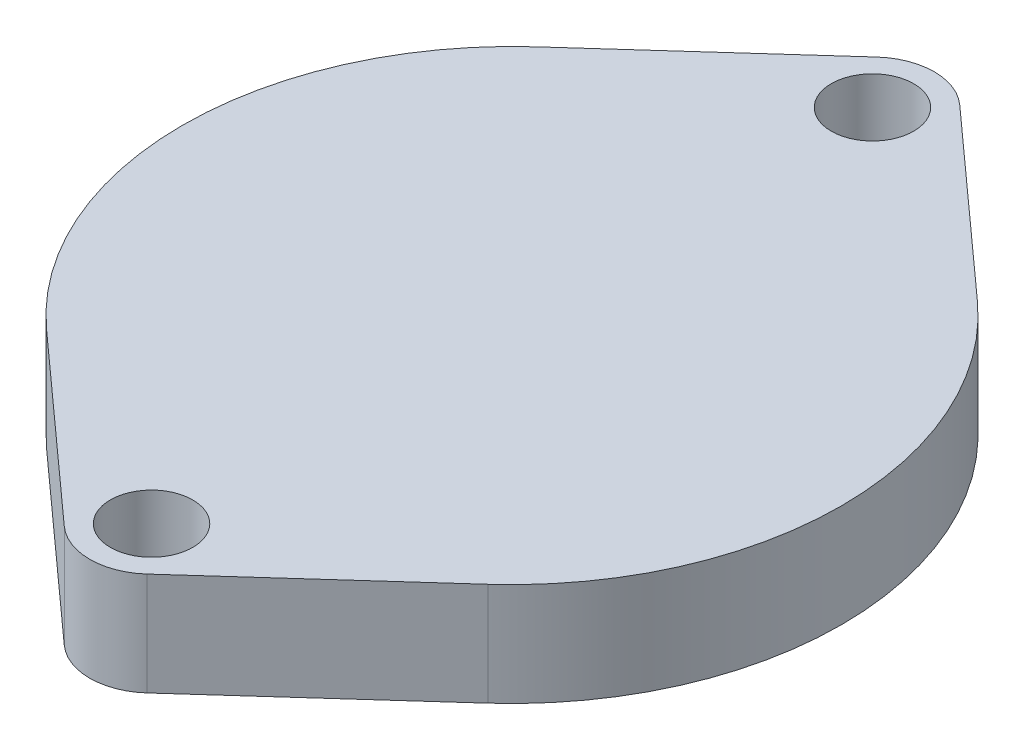
SolidWorks part; units mm, degrees
ref_plane "前视基准面" through (0, 0, 0) normal (0, 0, 1) x (1, 0, 0)
ref_plane "上视基准面" through (0, 0, 0) normal (0, 1, 0) x (1, 0, 0)
ref_plane "右视基准面" through (0, 0, 0) normal (1, 0, 0) x (0, 0, -1)
sketch "草图1" plane through (0, 0, 0) normal (0, 1, 0) x (1, 0, 0)
  line L0 (0, -17.5) -> (0, 17.5) construction
  line L1 (-2.0083, 19.7286) -> (-10.7112, 11.8857)
  line L2 (0, 0) -> (16, 0) construction
  line L3 (0, 4.4973) -> (0, -9.4013) construction
  line L4 (2.0083, 19.7286) -> (10.7112, 11.8857)
  line L5 (-2.0083, 19.7286) -> (-10.7112, 11.8857)
  line L6 (2.0083, 19.7286) -> (10.7112, 11.8857)
  line L7 (2.0083, -19.7286) -> (10.7112, -11.8857)
  line L8 (-2.0083, -19.7286) -> (-10.7112, -11.8857)
  line L9 (2.0083, -19.7286) -> (10.7112, -11.8857)
  line L10 (-2.0083, -19.7286) -> (-10.7112, -11.8857)
  arc A0 (-10.7112, 11.8857) -> (-10.7112, -11.8857) centre (0, 0) ccw
  circle A1 centre (0, 17.5) radius 2
  arc A3 (2.0083, 19.7286) -> (-2.0083, 19.7286) centre (0, 17.5) ccw
  arc A4 (10.7112, 11.8857) -> (10.7112, -11.8857) centre (0, 0) cw
  arc A5 (-10.7112, 11.8857) -> (-10.7112, -11.8857) centre (0, 0) ccw
  arc A6 (10.7112, 11.8857) -> (10.7112, -11.8857) centre (0, 0) cw
  arc A7 (2.0083, -19.7286) -> (-2.0083, -19.7286) centre (0, -17.5) cw
  circle A8 centre (0, -17.5) radius 2
  dimension "D1" = 32
  dimension "D3" = 4
  dimension "D4" = 3
  dimension "D2" = 17.5
extrude "凸台-拉伸1" add sketch "草图1" along normal blind 5 contours A7 L7 A4 L4 A3 L1 A0 L8 A1 A8
